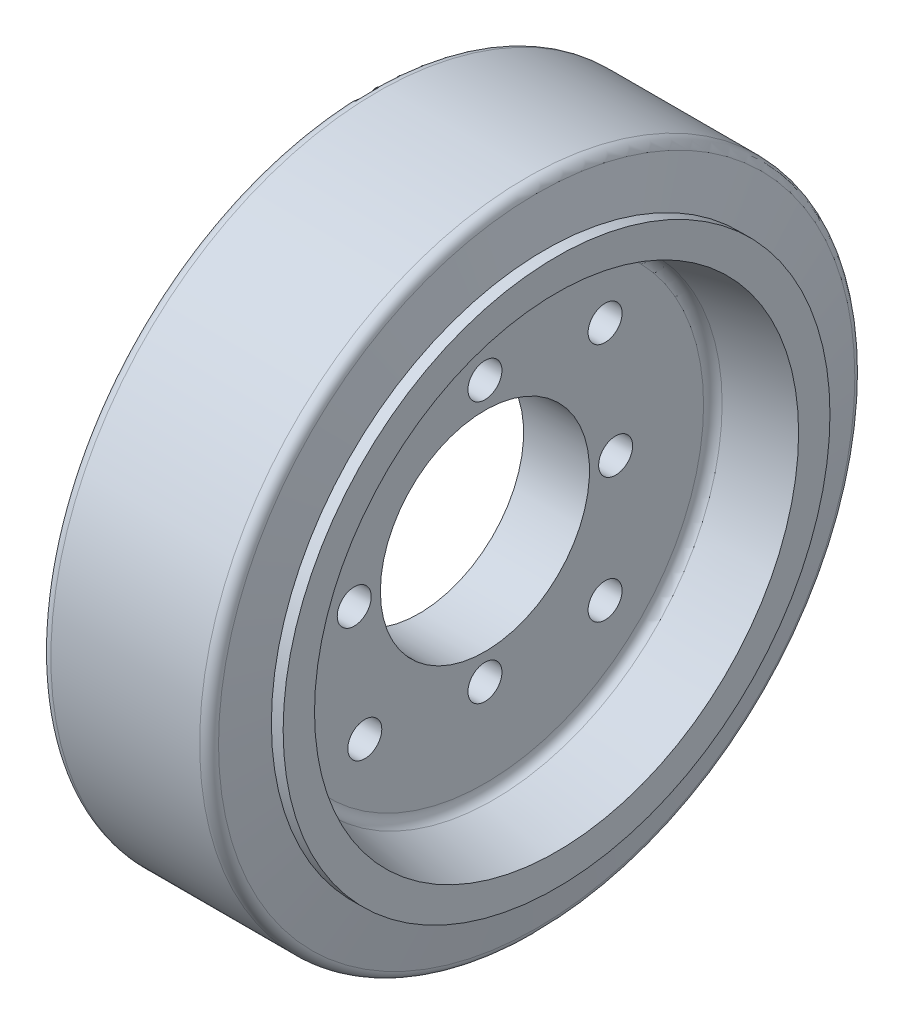
SolidWorks part; units mm, degrees
material "PUR"
ref_plane "Front Plane" through (0, 0, 0) normal (0, 0, 1) x (1, 0, 0)
ref_plane "Top Plane" through (0, 0, 0) normal (0, 1, 0) x (1, 0, 0)
ref_plane "Right Plane" through (0, 0, 0) normal (1, 0, 0) x (0, 0, -1)
sketch "Sketch1" plane through (0, 0, 0) normal (0, 0, 1) x (1, 0, 0)
  line L0 (-15.9, -62.5) -> (15.9, -62.5)
  line L1 (-15.9, -62.5) -> (-17.75, -52.3)
  line L2 (20, -46.3) -> (6.3, -43.45)
  line L3 (6.3, -43.45) -> (6.3, -17)
  line L4 (6.3, -17) -> (22.2, -15.75)
  line L5 (22.2, -15.75) -> (22.2, -10.05)
  line L6 (0, -62.5) -> (0, 0) construction
  line L7 (0, 0) -> (22.2, 0) construction
  line L8 (22.2, -10.05) -> (-22.2, -10.05)
  line L9 (-22.2, -15.75) -> (-22.2, -10.05)
  line L10 (-6.3, -17) -> (-22.2, -15.75)
  line L11 (-6.3, -43.45) -> (-6.3, -17)
  line L12 (-20, -46.3) -> (-6.3, -43.45)
  line L13 (-17.75, -52.3) -> (-20, -52.3)
  line L14 (-20, -52.3) -> (-20, -46.3)
  line L15 (15.9, -62.5) -> (17.75, -52.3)
  line L16 (17.75, -52.3) -> (20, -52.3)
  line L17 (20, -52.3) -> (20, -46.3)
  point P12 (0, -10.05)
  dimension "D1" = 44.4
  dimension "D2" = 40
  dimension "D3" = 20.1
  dimension "D4" = 31.5
  dimension "D5" = 125
  dimension "D6" = 6
  dimension "D7" = 15.9
  dimension "D8" = 1.85
  dimension "D9" = 2.25
  dimension "D10" = 16.2
  dimension "D11" = 2.85
  dimension "D12" = 34
revolve "Revolve1" add sketch "Sketch1" angle 360 about L7
fillet "Fillet1" radius 2 8 edges at (6.3, 0, 43.45) (6.3, 0, 17) (-6.3, 0, 17) (-6.3, 0, 43.45) (22.2, 0, 15.75) (-22.2, 0, 15.75) (-15.9, 0, 62.5) (15.9, 0, 62.5)
sketch "Sketch2" plane through (-6.3, 0, 0) normal (-1, 0, 0) x (0, 0, 1)
  circle A0 centre (0, 0) radius 20
  dimension "D1" = 40
extrude "Cut-Extrude1" cut sketch "Sketch2" against normal through all both and the other way through all
sketch "Sketch3" plane through (-6.3, 0, 0) normal (-1, 0, 0) x (0, 0, 1)
  circle A0 centre (0, 25) radius 3.25
  circle A1 centre (-25, 0) radius 3.25
  circle A2 centre (0, -25) radius 3.25
  circle A3 centre (25, 0) radius 3.25
  circle A4 centre (0, 0) radius 25 construction
  dimension "D1" = 50
  dimension "D2" = 6.5
extrude "Cut-Extrude2" cut sketch "Sketch3" against normal through all
hole_wizard "Ø6.5 (6.5) Diameter Hole1" positions "Sketch5" profile "Sketch4" hole size "Ø6.5" standard "ISO" end condition through all
sketch "Sketch5" plane through (-6.3, 0, 0) normal (-1, 0, 0) x (0, 0, 1)
  line L0 (-22.981, 22.981) -> (-22.981, -22.981)
  line L1 (-22.981, 22.981) -> (22.981, 22.981)
  line L2 (-22.981, -22.981) -> (22.981, -22.981)
  line L3 (22.981, 22.981) -> (22.981, -22.981)
  line L4 (-22.981, 22.981) -> (0, 0) construction
  line L5 (0, 0) -> (-13.4152, 0) construction
  line L7 (0, 0) -> (22.981, -22.981) construction
  point P0 (-22.981, 22.981)
  point P2 (-22.981, -22.981)
  point P4 (22.981, -22.981)
  point P6 (22.981, 22.981)
  dimension "D1" = 45
  dimension "D2" = 65
sketch "Sketch4" plane through (-6.3, 22.981, -22.981) normal (0, 1, 0) x (0, 0, 1)
  line L0 (0, 0) -> (0, 26.3)
  line L1 (0, 26.3) -> (3.25, 26.3)
  line L2 (3.25, 26.3) -> (3.25, 0)
  line L5 (3.25, 0) -> (0, 0)
  line L11 (0, -6.35) -> (0, 107.95) construction
  dimension "Thru Hole Dia." = 6.5
  dimension "Thru Hole Depth" = 26.3
move or copy body "Body-Move/Copy1" [suppressed] bodies to move or copy 101
